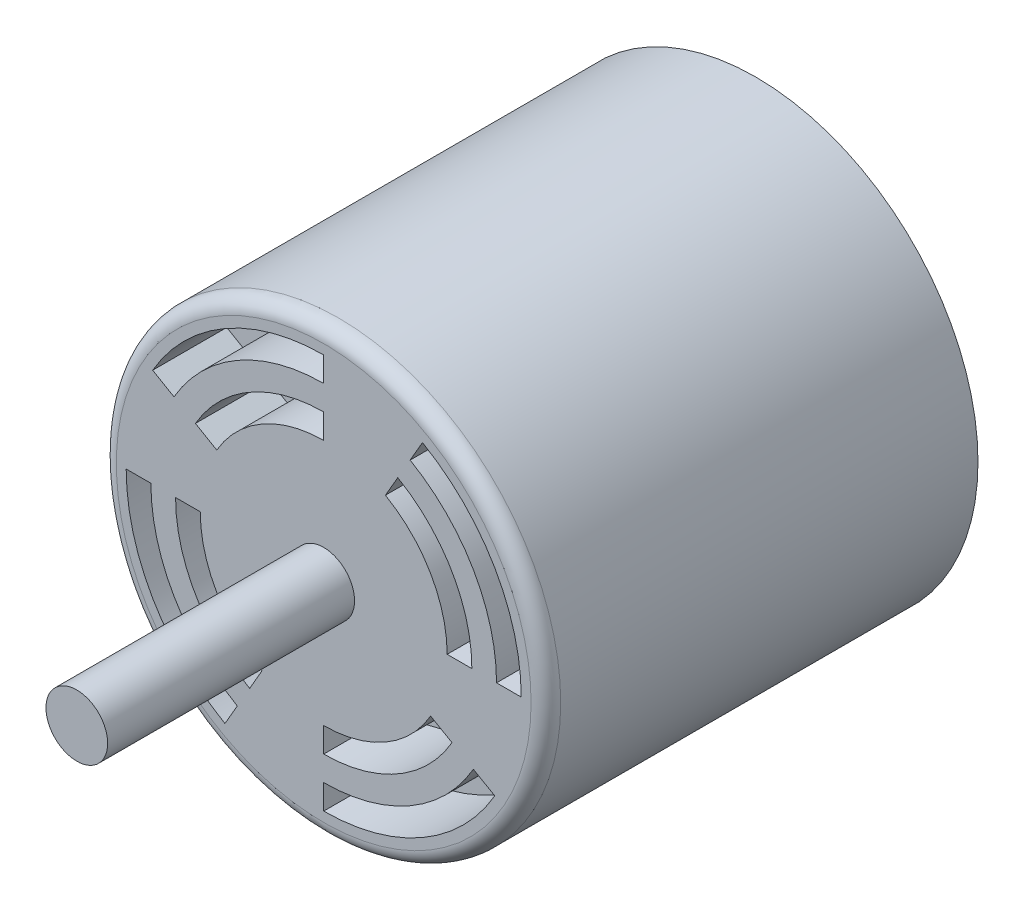
SolidWorks part; units mm, degrees
ref_plane "Front Plane" through (0, 0, 0) normal (0, 0, 1) x (1, 0, 0)
ref_plane "Top Plane" through (0, 0, 0) normal (0, 1, 0) x (1, 0, 0)
ref_plane "Right Plane" through (0, 0, 0) normal (1, 0, 0) x (0, 0, -1)
sketch "Sketch1" plane through (0, 0, 0) normal (0, 0, 1) x (1, 0, 0)
  circle A0 centre (0, 0) radius 22.86
  dimension "D1" = 45.72
extrude "Boss-Extrude1" add sketch "Sketch1" along normal blind 44.45
sketch "Sketch2" plane through (0, 0, 44.45) normal (0, 0, 1) x (1, 0, 0)
  circle A0 centre (0, 0) radius 3.175
  dimension "D1" = 6.35
extrude "Boss-Extrude2" add sketch "Sketch2" along normal blind 25.4
sketch "Sketch3" plane through (0, 0, 44.45) normal (0, 0, 1) x (1, 0, 0)
  line L0 (12.7, 0) -> (15.24, 0)
  line L1 (6.35, 10.9985) -> (7.62, 13.1982)
  line L2 (8.89, 15.3979) -> (10.16, 17.5976)
  line L3 (17.78, 0) -> (20.32, 0)
  line L4 (10.9985, -6.35) -> (13.1982, -7.62)
  line L5 (0, -12.7) -> (0, -15.24)
  line L6 (0, -17.78) -> (0, -20.32)
  line L7 (15.3979, -8.89) -> (17.5976, -10.16)
  line L8 (-6.35, -10.9985) -> (-7.62, -13.1982)
  line L9 (-12.7, 0) -> (-15.24, 0)
  line L10 (-17.78, 0) -> (-20.32, 0)
  line L11 (-8.89, -15.3979) -> (-10.16, -17.5976)
  line L12 (-10.9985, 6.35) -> (-13.1982, 7.62)
  line L13 (0, 12.7) -> (0, 15.24)
  line L14 (0, 17.78) -> (0, 20.32)
  line L15 (-15.3979, 8.89) -> (-17.5976, 10.16)
  arc A0 (12.7, 0) -> (6.35, 10.9985) centre (0, 0) ccw
  arc A1 (15.24, 0) -> (7.62, 13.1982) centre (0, 0) ccw
  arc A2 (20.32, 0) -> (10.16, 17.5976) centre (0, 0) ccw
  arc A3 (17.78, 0) -> (8.89, 15.3979) centre (0, 0) ccw
  circle A4 centre (0, 0) radius 20.32 construction
  circle A5 centre (0, 0) radius 17.78 construction
  circle A6 centre (0, 0) radius 15.24 construction
  circle A7 centre (0, 0) radius 12.7 construction
  arc A8 (0, -15.24) -> (13.1982, -7.62) centre (0, 0) ccw
  arc A9 (0, -12.7) -> (10.9985, -6.35) centre (0, 0) ccw
  arc A10 (0, -17.78) -> (15.3979, -8.89) centre (0, 0) ccw
  arc A11 (0, -20.32) -> (17.5976, -10.16) centre (0, 0) ccw
  arc A12 (-15.24, 0) -> (-7.62, -13.1982) centre (0, 0) ccw
  arc A13 (-12.7, 0) -> (-6.35, -10.9985) centre (0, 0) ccw
  arc A14 (-17.78, 0) -> (-8.89, -15.3979) centre (0, 0) ccw
  arc A15 (-20.32, 0) -> (-10.16, -17.5976) centre (0, 0) ccw
  arc A16 (0, 15.24) -> (-13.1982, 7.62) centre (0, 0) ccw
  arc A17 (0, 12.7) -> (-10.9985, 6.35) centre (0, 0) ccw
  arc A18 (0, 17.78) -> (-15.3979, 8.89) centre (0, 0) ccw
  arc A19 (0, 20.32) -> (-17.5976, 10.16) centre (0, 0) ccw
  point P44 (0, 0)
  dimension "D1" = 2.54
  dimension "D4" = 4
  dimension "D2" = 7.62
  dimension "D3" = 5.08
extrude "Cut-Extrude1" cut sketch "Sketch3" against normal blind 7.62
fillet "Fillet1" radius 1.524 1 edges at (22.86, 0, 44.45)
